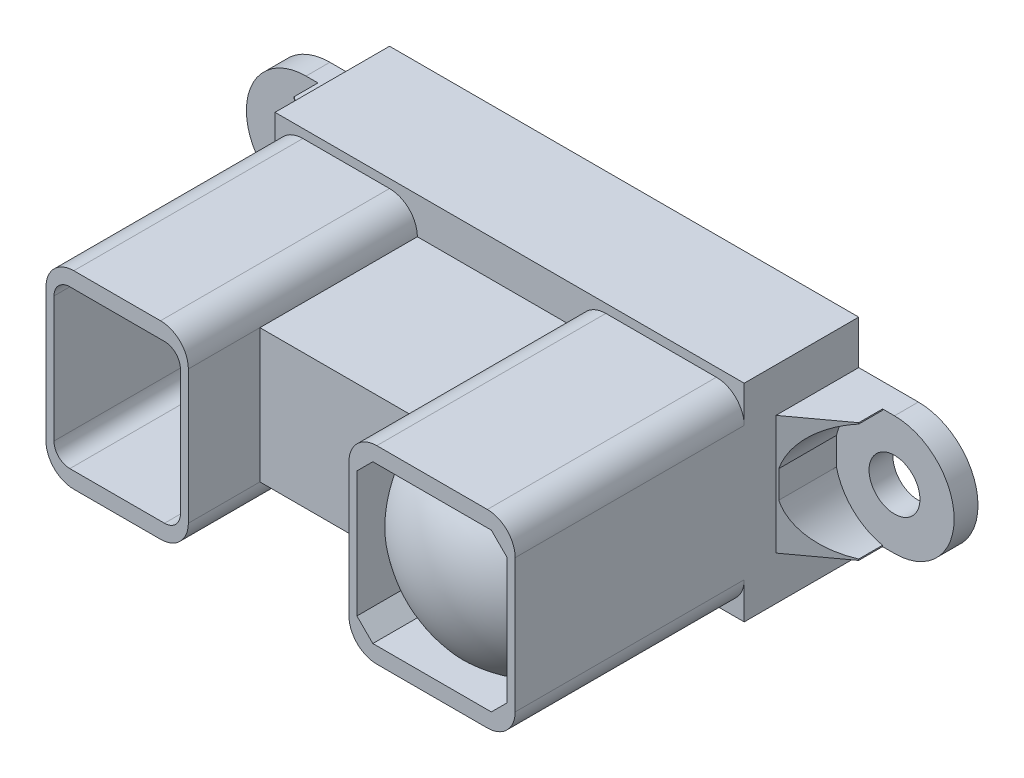
SolidWorks part; units mm, degrees
ref_plane "Front Plane" through (0, 0, 0) normal (0, 0, 1) x (1, 0, 0)
ref_plane "Top Plane" through (0, 0, 0) normal (0, 1, 0) x (1, 0, 0)
ref_plane "Right Plane" through (0, 0, 0) normal (1, 0, 0) x (0, 0, -1)
sketch "Sketch1" plane through (0, 0, 0) normal (0, 0, 1) x (1, 0, 0)
  line L0 (-39.6791, 6.3068) -> (-35.9291, 6.3068)
  line L1 (-35.9291, 9.0568) -> (-6.4291, 9.0568)
  line L2 (-35.9291, 9.0568) -> (-35.9291, 6.3068)
  line L3 (-35.9291, -3.9432) -> (-26.2291, -3.9432)
  line L4 (-6.4291, 9.0568) -> (-6.4291, 6.3068)
  line L5 (-39.6791, -1.1932) -> (-35.9291, -1.1932)
  line L6 (-2.6791, 6.3068) -> (-6.4291, 6.3068)
  line L7 (-2.6791, -1.1932) -> (-6.4291, -1.1932)
  line L8 (-26.2291, -3.9432) -> (-26.2291, -3.0794)
  line L9 (-25.4791, -1.6432) -> (-16.8791, -1.6432)
  line L10 (-16.1291, -3.0794) -> (-16.1291, -3.9432)
  line L11 (-16.1291, -3.9432) -> (-6.4291, -3.9432)
  line L12 (-35.9291, -1.1932) -> (-35.9291, -3.9432)
  line L13 (-6.4291, -1.1932) -> (-6.4291, -3.9432)
  arc A0 (-39.6791, 6.3068) -> (-39.6791, -1.1932) centre (-39.6791, 2.5568) ccw
  arc A1 (-2.6791, -1.1932) -> (-2.6791, 6.3068) centre (-2.6791, 2.5568) ccw
  circle A2 centre (-39.6791, 2.5568) radius 1.6
  circle A3 centre (-2.6791, 2.5568) radius 1.6
  arc A4 (-26.2291, -3.0794) -> (-25.4791, -1.6432) centre (-27.2291, -1.6432) ccw
  arc A5 (-16.8791, -1.6432) -> (-16.1291, -3.0794) centre (-15.1291, -1.6432) ccw
  dimension "D3" = 7.5
  dimension "D4" = 7.5
  dimension "D5" = 3.2
  dimension "D6" = 3.2
  dimension "D16" = 1.75
  dimension "D17" = 1.75
  dimension "D1" = 29.5
  dimension "D2" = 13
  dimension "D7" = 37
  dimension "D8" = 3.75
  dimension "D9" = 6.5
  dimension "D10" = 6.5
  dimension "D11" = 10.1
  dimension "D12" = 9.7
  dimension "D13" = 4.2
extrude "Boss-Extrude1" add sketch "Sketch1" along normal blind 7.2
sketch "Sketch3" plane through (0, -3.9432, 0) normal (0, -1, 0) x (1, 0, 0)
  line L0 (-44.5435, 1.5) -> (-38.9291, 1.5)
  line L1 (-38.9291, 1.5) -> (-38.9291, 3)
  line L2 (-38.9291, 3) -> (-35.9291, 5.2)
  line L3 (-35.9291, 7.2) -> (-35.9291, 0) construction
  line L4 (-35.9291, 5.2) -> (-35.9291, 8.3789)
  line L5 (-35.9291, 8.3789) -> (-44.5435, 8.3789)
  line L6 (-44.5435, 8.3789) -> (-44.5435, 1.5)
  line L7 (-43.4291, 0) -> (-39.6791, 0) construction
  line L8 (-39.6791, 7.2) -> (-35.9291, 7.2) construction
  line L10 (-21.1791, 7.2) -> (-21.1791, 0) construction
  line L11 (-25.4791, 7.2) -> (-16.8791, 7.2) construction
  line L12 (-25.4791, 0) -> (-16.8791, 0) construction
  line L13 (2.1853, 8.3789) -> (2.1853, 1.5)
  line L14 (-6.4291, 8.3789) -> (2.1853, 8.3789)
  line L15 (-6.4291, 5.2) -> (-6.4291, 8.3789)
  line L16 (-3.4291, 3) -> (-6.4291, 5.2)
  line L17 (-3.4291, 1.5) -> (-3.4291, 3)
  line L18 (2.1853, 1.5) -> (-3.4291, 1.5)
  dimension "D1" = 1.5
  dimension "D2" = 2
  dimension "D3" = 1.5
  dimension "D4" = 3
extrude "Cut-Extrude1" cut sketch "Sketch3" against normal through all
sketch "Sketch4" plane through (0, 0, 1.5) normal (0, 0, 1) x (1, 0, 0)
  line L0 (-36.0291, 3.417) -> (-36.0291, 1.6966)
  line L1 (-35.9291, 9.0568) -> (-35.9291, -3.9432) construction
  line L2 (-6.3291, 3.417) -> (-6.3291, 1.6966)
  line L3 (-6.4291, -3.9432) -> (-6.4291, 9.0568) construction
  arc A0 (-36.0291, 3.417) -> (-36.0291, 1.6966) centre (-39.6791, 2.5568) ccw
  arc A1 (-6.3291, 1.6966) -> (-6.3291, 3.417) centre (-2.6791, 2.5568) ccw
  point P10 (-35.9291, 2.5568)
  dimension "D1" = 7.5
  dimension "D2" = 7.5
  dimension "D3" = 180
  dimension "D4" = 0.1
  dimension "D5" = 0.1
extrude "Cut-Extrude2" cut sketch "Sketch4" along normal through all
sketch "Sketch5" plane through (0, 0, 7.2) normal (0, 0, 1) x (1, 0, 0)
  line L0 (-6.4291, 9.0568) -> (-35.9291, 9.0568) construction
  line L1 (-34.1791, 8.5068) -> (-28.7291, 8.5068)
  line L2 (-35.9291, 6.7568) -> (-35.9291, -1.6432)
  line L3 (-34.1791, -3.3932) -> (-28.7291, -3.3932)
  line L4 (-26.9791, 6.7568) -> (-26.9791, -1.6432)
  line L5 (-15.1291, 8.5068) -> (-8.1791, 8.5068)
  line L6 (-16.8791, 6.7568) -> (-16.8791, -1.6432)
  line L7 (-15.1291, -3.3932) -> (-8.1791, -3.3932)
  line L8 (-6.4291, 6.7568) -> (-6.4291, -1.6432)
  line L9 (-34.4291, 7.5068) -> (-28.4791, 7.5068)
  line L10 (-35.4291, 6.5068) -> (-35.4291, -1.3932)
  line L11 (-34.4291, -2.3932) -> (-28.4791, -2.3932)
  line L12 (-27.4791, 6.5068) -> (-27.4791, -1.3932)
  line L13 (-15.3791, 7.5068) -> (-7.9291, 7.5068)
  line L14 (-16.3791, 6.5068) -> (-16.3791, -1.3932)
  line L15 (-15.3791, -2.3932) -> (-7.9291, -2.3932)
  line L16 (-6.9291, 6.5068) -> (-6.9291, -1.3932)
  line L17 (-35.9291, 9.0568) -> (-35.9291, -3.9432) construction
  line L18 (-6.4291, -3.9432) -> (-6.4291, 9.0568) construction
  line L19 (-16.3791, 6.5068) -> (-15.3791, 7.5068)
  line L20 (-7.9291, 7.5068) -> (-6.9291, 6.5068)
  line L21 (-7.9291, -2.3932) -> (-6.9291, -1.3932)
  line L22 (-16.3791, -1.3932) -> (-15.3791, -2.3932)
  arc A0 (-15.1291, 8.5068) -> (-16.8791, 6.7568) centre (-15.1291, 6.7568) ccw
  arc A1 (-8.1791, 8.5068) -> (-6.4291, 6.7568) centre (-8.1791, 6.7568) cw
  arc A2 (-8.1791, -3.3932) -> (-6.4291, -1.6432) centre (-8.1791, -1.6432) ccw
  arc A3 (-16.8791, -1.6432) -> (-15.1291, -3.3932) centre (-15.1291, -1.6432) ccw
  arc A4 (-35.9291, -1.6432) -> (-34.1791, -3.3932) centre (-34.1791, -1.6432) ccw
  arc A5 (-28.7291, -3.3932) -> (-26.9791, -1.6432) centre (-28.7291, -1.6432) ccw
  arc A6 (-28.7291, 8.5068) -> (-26.9791, 6.7568) centre (-28.7291, 6.7568) cw
  arc A7 (-34.1791, 8.5068) -> (-35.9291, 6.7568) centre (-34.1791, 6.7568) ccw
  arc A8 (-35.4291, -1.3932) -> (-34.4291, -2.3932) centre (-34.4291, -1.3932) ccw
  arc A9 (-28.4791, -2.3932) -> (-27.4791, -1.3932) centre (-28.4791, -1.3932) ccw
  arc A10 (-28.4791, 7.5068) -> (-27.4791, 6.5068) centre (-28.4791, 6.5068) cw
  arc A11 (-34.4291, 7.5068) -> (-35.4291, 6.5068) centre (-34.4291, 6.5068) ccw
  point P12 (-16.3791, 7.5068)
  point P13 (-6.9291, -2.3932)
  point P14 (-16.3791, -2.3932)
  point P15 (-6.9291, 7.5068)
  point P24 (-16.8791, 8.5068)
  point P27 (-6.4291, 8.5068)
  point P30 (-6.4291, -3.3932)
  point P35 (-35.9291, -3.3932)
  point P40 (-26.9791, 8.5068)
  point P43 (-35.9291, 8.5068)
  dimension "D9" = 1.75
  dimension "D18" = 1
  dimension "D1" = 11.9
  dimension "D2" = 11.9
  dimension "D3" = 0.55
  dimension "D4" = 0.55
  dimension "D5" = 0
  dimension "D6" = 0
  dimension "D7" = 8.95
  dimension "D8" = 10.45
  dimension "D10" = 0.5
  dimension "D11" = 0.5
  dimension "D12" = 0.5
  dimension "D13" = 0.5
  dimension "D14" = 1
  dimension "D15" = 1
  dimension "D16" = 1
  dimension "D17" = 1
  dimension "D19" = 1
  dimension "D20" = 45
  dimension "D21" = 1
  dimension "D22" = 45
  dimension "D23" = 1
  dimension "D24" = 45
  dimension "D25" = 1
  dimension "D26" = 45
extrude "Boss-Extrude4" add sketch "Sketch5" along normal blind 14.4
sketch "Sketch6" plane through (0, 0, 7.2) normal (0, 0, 1) x (1, 0, 0)
  line L0 (-26.9791, -1.6432) -> (-26.9791, 6.7568) construction
  line L1 (-26.9791, 6.7568) -> (-16.8791, 6.7568)
  line L2 (-26.9791, 6.7568) -> (-26.9791, -1.6432)
  line L3 (-26.9791, -1.6432) -> (-16.8791, -1.6432)
  line L4 (-16.8791, 6.7568) -> (-16.8791, -1.6432)
  line L5 (-16.8791, 6.7568) -> (-16.8791, -1.6432) construction
  circle A0 centre (-39.6791, 2.5568) radius 1.6 construction
  dimension "D1" = 8.4
  dimension "D2" = 4.2
extrude "Boss-Extrude5" add sketch "Sketch6" along normal blind 9.9
ref_axis "Axis1" through (-31.4541, 8.5068, 7.2) along (0, -1, 0)
sketch "Sketch7" plane through (0, 0, 7.2) normal (0, 0, 1) x (1, 0, 0)
  line L0 (-31.4541, 8.5068) -> (-31.4541, -2.3932) construction
  line L1 (-31.4541, 6.5274) -> (-31.4541, -1.2726)
  line L3 (-27.4791, -1.3932) -> (-27.4791, 6.5068) construction
  arc A0 (-31.4541, 6.5274) -> (-31.4541, -1.2726) centre (-31.4541, 2.6274) cw
  dimension "D1" = 3.975
  dimension "D2" = 3.9
revolve "Revolve1" add sketch "Sketch7" angle 180 about axis through (-31.4541, 8.5068, 7.2) along (0, -1, 0)
ref_plane "Plane4" through (-11.6541, 0, 0) normal (1, 0, 0) x (0, 0, -1)
ref_plane "Plane5" through (0, 2.5568, 0) normal (0, 1, 0) x (1, 0, 0)
ref_axis "Axis4" through (-11.6541, 2.5568, 6.48) along (0, 0, 1)
sketch "Sketch11" plane through (-11.6541, 0, 0) normal (1, 0, 0) x (0, 0, -1)
  line L0 (4.0975, 2.5568) -> (-4.0975, 2.5568) construction
  line L1 (-17.85, 9.0068) -> (-17.85, 2.5568)
  line L2 (-21.6, -1.6432) -> (-21.6, 6.7568) construction
  line L3 (-17.85, 2.5568) -> (-21.5228, 2.5568)
  line L4 (-21.6, 8.5068) -> (-7.2, 8.5068) construction
  arc A0 (-17.85, 9.0068) -> (-21.5228, 2.5568) centre (-14.0228, 2.5568) ccw
  dimension "D2" = 15
  dimension "D1" = 3.75
  dimension "D3" = 0.5
revolve "Revolve7" add sketch "Sketch11" angle 360 about axis through (-11.6541, 2.5568, 6.48) along (0, 0, 1)
sketch "Sketch12" plane through (0, 0, 21.6) normal (0, 0, 1) x (1, 0, 0)
  line L0 (-8.1791, 8.5068) -> (-15.1291, 8.5068) construction
  line L1 (-6.4291, -1.6432) -> (-6.4291, 6.7568) construction
  line L2 (-15.1291, -3.3932) -> (-8.1791, -3.3932) construction
  line L3 (-16.8791, 6.7568) -> (-16.8791, -1.6432) construction
  line L4 (-9.1641, 8.5068) -> (-14.1441, 8.5068)
  line L5 (-6.4291, -1.225) -> (-6.4291, 6.3386)
  line L6 (-14.1441, -3.3932) -> (-9.1641, -3.3932)
  line L7 (-16.8791, 6.3386) -> (-16.8791, -1.225)
  arc A8 (-16.8791, 6.3386) -> (-16.8791, -1.225) centre (-11.6541, 2.5568) ccw construction
  arc A9 (-16.8791, 6.3386) -> (-16.8791, -1.225) centre (-11.6541, 2.5568) ccw
  arc A10 (-9.1641, 8.5068) -> (-14.1441, 8.5068) centre (-11.6541, 2.5568) ccw construction
  arc A11 (-9.1641, 8.5068) -> (-14.1441, 8.5068) centre (-11.6541, 2.5568) ccw
  arc A12 (-14.1441, -3.3932) -> (-9.1641, -3.3932) centre (-11.6541, 2.5568) ccw construction
  arc A13 (-14.1441, -3.3932) -> (-9.1641, -3.3932) centre (-11.6541, 2.5568) ccw
  arc A14 (-6.4291, -1.225) -> (-6.4291, 6.3386) centre (-11.6541, 2.5568) ccw construction
  arc A15 (-6.4291, -1.225) -> (-6.4291, 6.3386) centre (-11.6541, 2.5568) ccw
extrude "Cut-Extrude3" cut sketch "Sketch12" against normal blind 4
sketch "Sketch13" plane through (0, 0, 0) normal (0, 0, -1) x (-1, 0, 0)
  line L0 (6.9291, 8.5568) -> (35.4291, 8.5568)
  line L1 (35.4291, 8.5568) -> (35.4291, -3.4432)
  line L2 (35.4291, -3.4432) -> (6.9291, -3.4432)
  line L3 (6.9291, -3.4432) -> (6.9291, 8.5568)
  line L4 (6.4291, 6.3068) -> (6.4291, 9.0568) construction
  line L5 (6.4291, 9.0568) -> (35.9291, 9.0568) construction
  line L6 (16.1291, -3.9432) -> (6.4291, -3.9432) construction
  line L7 (35.9291, 9.0568) -> (35.9291, 6.3068) construction
  dimension "D1" = 0.5
  dimension "D2" = 0.5
  dimension "D3" = 0.5
  dimension "D4" = 0.5
extrude "Cut-Extrude4" cut sketch "Sketch13" against normal blind 3.3
sketch "Sketch14" plane through (0, 0, 3.3) normal (0, 0, -1) x (-1, 0, 0)
  line L0 (26.2291, -3.9432) -> (26.2291, -3.0794) construction
  line L1 (25.4791, -1.6432) -> (16.8791, -1.6432) construction
  line L2 (16.1291, -3.0794) -> (16.1291, -3.9432) construction
  line L3 (26.2291, -3.9432) -> (26.2291, -3.0794)
  line L4 (25.4791, -1.6432) -> (16.8791, -1.6432)
  line L5 (16.1291, -3.0794) -> (16.1291, -3.9432)
  line L6 (16.1291, -3.9432) -> (16.1291, -8.8432)
  line L7 (17.1291, -9.8432) -> (25.2291, -9.8432)
  line L8 (26.2291, -8.8432) -> (26.2291, -3.9432)
  line L9 (6.4291, 9.0568) -> (35.9291, 9.0568) construction
  arc A0 (25.4791, -1.6432) -> (26.2291, -3.0794) centre (27.2291, -1.6432) ccw construction
  arc A1 (16.1291, -3.0794) -> (16.8791, -1.6432) centre (15.1291, -1.6432) ccw construction
  arc A2 (25.4791, -1.6432) -> (26.2291, -3.0794) centre (27.2291, -1.6432) ccw
  arc A3 (16.1291, -3.0794) -> (16.8791, -1.6432) centre (15.1291, -1.6432) ccw
  arc A4 (25.2291, -9.8432) -> (26.2291, -8.8432) centre (25.2291, -8.8432) ccw
  arc A5 (16.1291, -8.8432) -> (17.1291, -9.8432) centre (17.1291, -8.8432) ccw
  dimension "D2" = 1
  dimension "D1" = 18.9
extrude "Boss-Extrude6" add sketch "Sketch14" against normal blind 1.2
ref_plane "Plane6" through (-21.1791, 0, 0) normal (-1, 0, 0) x (0, 0, 1)
sketch "Sketch15" plane through (-21.1791, 0, 0) normal (-1, 0, 0) x (0, 0, 1)
  line L0 (6.5, -2.1432) -> (4.5, -2.1432)
  line L1 (4.5, -2.1432) -> (4.5, -9.7432)
  line L2 (4.5, -9.7432) -> (7.1, -9.7432)
  line L3 (7.1, -9.7432) -> (7.1, -8.2432)
  line L4 (7.1, -8.2432) -> (8.1, -8.2432) construction
  line L5 (8.1, -8.2432) -> (8.1, -9.7432)
  line L6 (8.1, -9.7432) -> (9.3, -9.7432)
  line L7 (9.3, -9.7432) -> (9.3, -3.7432)
  line L8 (9.3, -3.7432) -> (8.1, -3.7432)
  line L9 (8.1, -3.7432) -> (6.5, -2.1432)
  line L10 (4.5, -8.8432) -> (4.5, -3.9432) construction
  line L11 (4.5, -9.8432) -> (3.3, -9.8432) construction
  arc A0 (8.1, -8.2432) -> (7.1, -8.2432) centre (7.6, -8.2432) ccw
  point P2 (7.6, -8.2432)
  dimension "D1" = 4.8
  dimension "D2" = 6
  dimension "D3" = 7.6
  dimension "D4" = 1.6
  dimension "D5" = 1.7
  dimension "D6" = 0
  dimension "D7" = 0.1
  dimension "D8" = 1
  dimension "D9" = 1.5
  dimension "D10" = 2
  dimension "D11" = 1.2
extrude "Boss-Extrude7" add sketch "Sketch15" along normal blind 3.95 and the other way blind 3.95
sketch "Sketch16" plane through (0, -9.7432, 0) normal (0, -1, 0) x (1, 0, 0)
  line L0 (-17.2291, 9.3) -> (-25.1291, 9.3) construction
  line L1 (-24.6291, 8.8) -> (-17.7291, 8.8)
  line L2 (-24.6291, 8.8) -> (-24.6291, 5)
  line L3 (-24.6291, 5) -> (-17.7291, 5)
  line L4 (-17.7291, 8.8) -> (-17.7291, 5)
  line L5 (-25.1291, 4.5) -> (-25.1291, 7.1) construction
  line L6 (-17.2291, 4.5) -> (-25.1291, 4.5) construction
  line L7 (-17.2291, 8.1) -> (-17.2291, 9.3) construction
  dimension "D1" = 0.5
  dimension "D2" = 0.5
  dimension "D3" = 0.5
  dimension "D4" = 0.5
extrude "Cut-Extrude5" cut sketch "Sketch16" against normal blind 5.5
ref_point "Point2"
sketch "Sketch18" plane through (0, -4.2432, 0) normal (0, -1, 0) x (1, 0, 0)
  circle A0 centre (-21.1791, 6.9) radius 0.5
  circle A1 centre (-19.1791, 6.9) radius 0.5
  circle A2 centre (-23.1791, 6.9) radius 0.5
  dimension "D1" = 2
  dimension "D2" = 2
extrude "Boss-Extrude8" add sketch "Sketch18" along normal blind 5.25
fillet "Fillet1" radius 0.5 3 edges at (-19.1791, -9.4932, 6.4) (-21.1791, -9.4932, 6.4) (-23.1791, -9.4932, 6.4)
